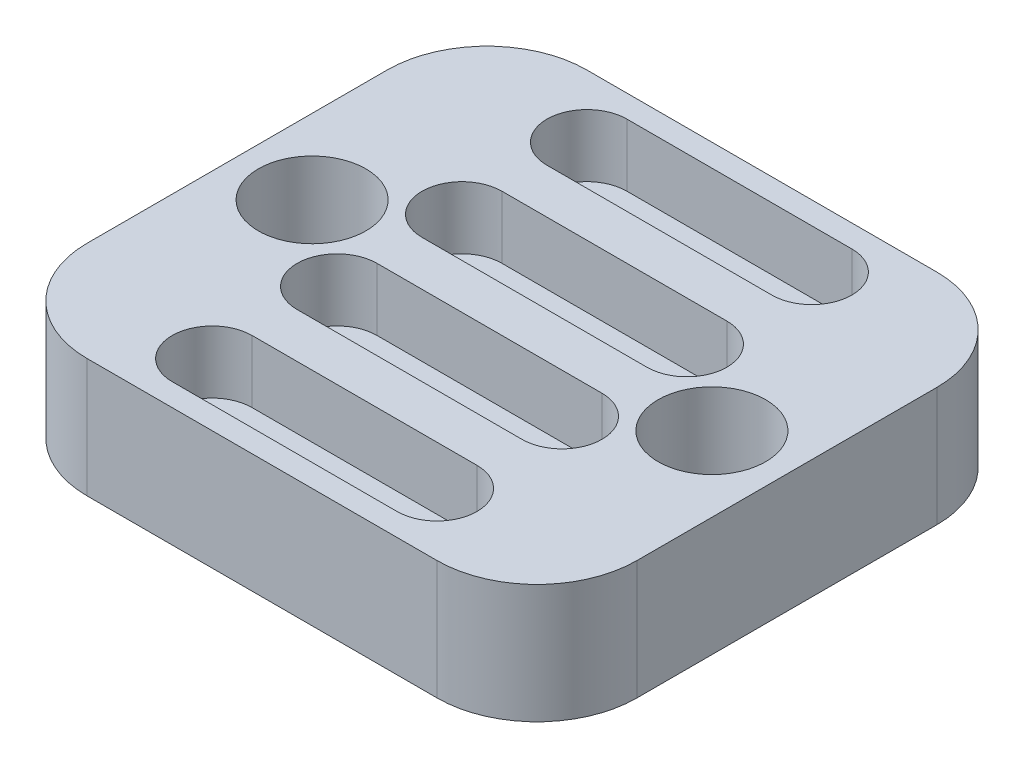
SolidWorks part; units mm, degrees
material "6061-T6 (SS)"
ref_plane "Front Plane" through (0, 0, 0) normal (0, 0, 1) x (1, 0, 0)
ref_plane "Top Plane" through (0, 0, 0) normal (0, 1, 0) x (1, 0, 0)
ref_plane "Right Plane" through (0, 0, 0) normal (1, 0, 0) x (0, 0, -1)
sketch "Sketch1" plane through (0, 0, 0) normal (1, 0, 0) x (0, 0, -1)
  line L0 (5.9, 4.7625) -> (5.9, 2.2625)
  line L1 (0, 0) -> (20, 0)
  line L2 (0, 0) -> (0, 4.7625)
  line L3 (0, 4.7625) -> (20, 4.7625)
  line L4 (20, 0) -> (20, 4.7625)
  line L5 (0.9, 4.7625) -> (4.1, 4.7625)
  line L6 (0.9, 4.7625) -> (0.9, 2.2625)
  line L7 (0.9, 2.2625) -> (4.1, 2.2625)
  line L8 (4.1, 4.7625) -> (4.1, 2.2625)
  line L9 (5.9, 2.2625) -> (9.1, 2.2625)
  line L10 (9.1, 4.7625) -> (9.1, 2.2625)
  line L11 (10.9, 4.7625) -> (10.9, 2.2625)
  line L12 (10.9, 2.2625) -> (14.1, 2.2625)
  line L13 (14.1, 4.7625) -> (14.1, 2.2625)
  line L14 (15.9, 4.7625) -> (15.9, 2.2625)
  line L15 (15.9, 2.2625) -> (19.1, 2.2625)
  line L16 (19.1, 4.7625) -> (19.1, 2.2625)
  line L29 (19.1, 2.2625) -> (20, 2.2625) construction
  line L30 (0.9, 2.2625) -> (0, 2.2625) construction
  point P8 (2.5, 2.2625)
  point P26 (7.5, 2.2625)
  dimension "D2" = 4.7625
  dimension "D3" = 2.5
  dimension "D4" = 3.2
  dimension "D5" = 0.9
  dimension "D7" = 5
  dimension "D6" = 4
extrude "Boss-Extrude1" add sketch "Sketch1" along normal mid plane 9
sketch "Sketch3" plane through (0, 0, 0) normal (0, -1, 0) x (1, 0, 0)
  line L0 (0, 0) -> (0, -20) construction
  line L1 (4.5, 0) -> (11, 0)
  line L2 (4.5, 0) -> (4.5, -20)
  line L3 (4.5, -20) -> (11, -20)
  line L4 (11, 0) -> (11, -20)
  line L5 (4.5, -20) -> (-4.5, -20) construction
  line L6 (-4.5, -20) -> (-11, -20)
  line L7 (-11, 0) -> (-11, -20)
  line L8 (-4.5, 0) -> (-11, 0)
  line L9 (-4.5, 0) -> (-4.5, -20)
  line L10 (8, 0) -> (8, -20) construction
  circle A1 centre (8, -10) radius 2.1527
  circle A4 centre (-8, -10) radius 2.1527
  dimension "D2" = 4.3053
  dimension "D1" = 6.5
  dimension "D5" = 3.5
extrude "Boss-Extrude2" add sketch "Sketch3" against normal up to surface (4.7625 mm away) up to face at (0, 4.7625, -0.45)
sketch "Sketch4" plane through (0, 4.7625, 0) normal (0, 1, 0) x (1, 0, 0)
  line L0 (0, 0) -> (0, 20) construction
  line L1 (11, 0) -> (-11, 0) construction
  line L2 (11, 20) -> (-11, 20) construction
  line L3 (4.5, 4.1) -> (-4.5, 4.1) construction
  line L4 (4.5, 0.9) -> (4.5, 4.1) construction
  line L5 (4.5, 0.9) -> (4.5, 4.1)
  line L6 (4.5, 5.9) -> (4.5, 9.1)
  line L7 (4.5, 10.9) -> (4.5, 14.1)
  line L8 (4.5, 15.9) -> (4.5, 19.1)
  line L17 (-4.5, 15.9) -> (-4.5, 19.1)
  line L18 (-4.5, 10.9) -> (-4.5, 14.1)
  line L19 (-4.5, 5.9) -> (-4.5, 9.1)
  line L20 (-4.5, 0.9) -> (-4.5, 4.1)
  line L21 (4.5, 25.9) -> (4.5, 29.1) [skipped]
  line L22 (4.5, 30.9) -> (4.5, 34.1) [skipped]
  line L23 (4.5, 35.9) -> (4.5, 39.1) [skipped]
  line L24 (4.5, 20.9) -> (4.5, 24.1) [skipped]
  arc A0 (4.5, 0.9) -> (4.5, 4.1) centre (4.5, 2.5) ccw
  arc A1 (4.5, 5.9) -> (4.5, 9.1) centre (4.5, 7.5) ccw
  arc A2 (4.5, 10.9) -> (4.5, 14.1) centre (4.5, 12.5) ccw
  arc A3 (4.5, 15.9) -> (4.5, 19.1) centre (4.5, 17.5) ccw
  arc A12 (-4.5, 15.9) -> (-4.5, 19.1) centre (-4.5, 17.5) cw
  arc A13 (-4.5, 10.9) -> (-4.5, 14.1) centre (-4.5, 12.5) cw
  arc A14 (-4.5, 5.9) -> (-4.5, 9.1) centre (-4.5, 7.5) cw
  arc A15 (-4.5, 0.9) -> (-4.5, 4.1) centre (-4.5, 2.5) cw
  arc A16 (4.5, 25.9) -> (4.5, 29.1) centre (4.5, 27.5) ccw [skipped]
  arc A17 (4.5, 30.9) -> (4.5, 34.1) centre (4.5, 32.5) ccw [skipped]
  arc A18 (4.5, 35.9) -> (4.5, 39.1) centre (4.5, 37.5) ccw [skipped]
  arc A19 (4.5, 20.9) -> (4.5, 24.1) centre (4.5, 22.5) ccw [skipped]
  dimension "D1" = 8
extrude "Cut-Extrude1" cut sketch "Sketch4" against normal up to surface (2.5 mm away) up to face at (0, 2.2625, -2.5)
fillet "Fillet1" radius 4 4 edges at (11, 2.3813, -20) (11, 2.3812, 0) (-11, 2.3813, 0) (-11, 2.3812, -20)
equation "\"D2@Sketch1\"=.1875in"
